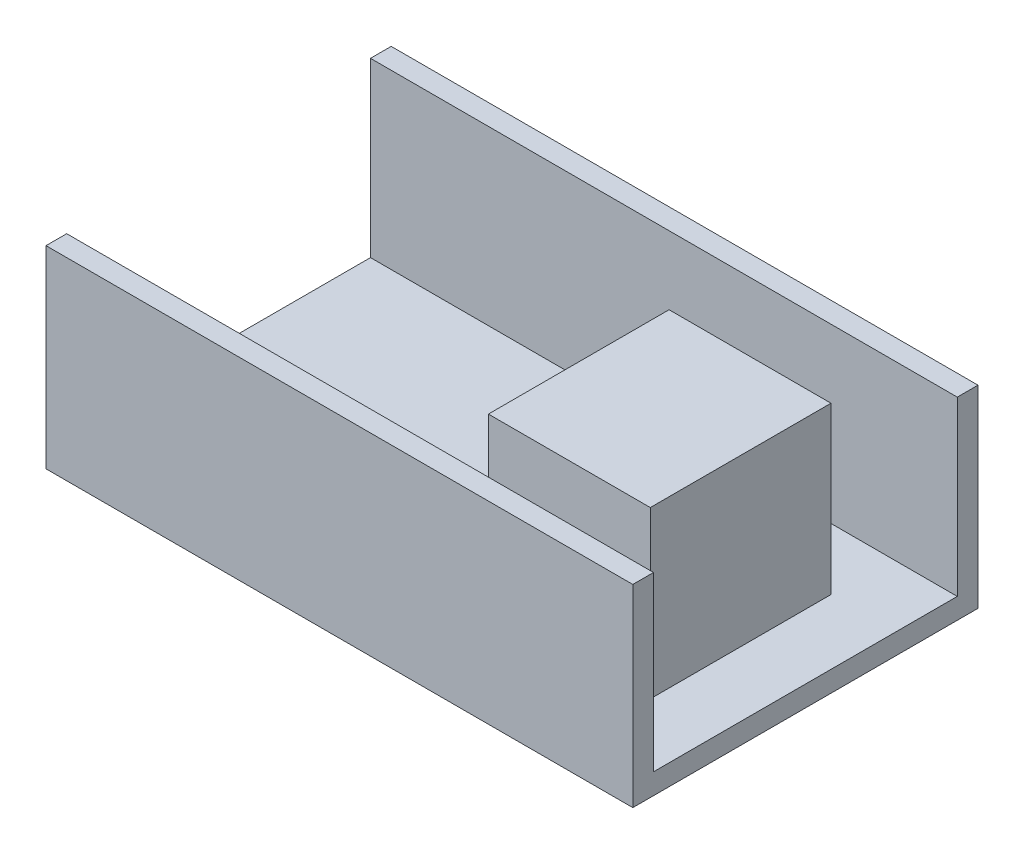
SolidWorks part; units mm, degrees
ref_plane "前视基准面" through (0, 0, 0) normal (0, 0, 1) x (1, 0, 0)
ref_plane "上视基准面" through (0, 0, 0) normal (0, 1, 0) x (1, 0, 0)
ref_plane "右视基准面" through (0, 0, 0) normal (1, 0, 0) x (0, 0, -1)
sketch "草图1" plane through (0, 0, 0) normal (1, 0, 0) x (0, 0, -1)
  line L0 (25, 28) -> (25, 0)
  line L1 (0, 0) -> (0, 41.8298) construction
  line L2 (-25, 28) -> (-25, 0)
  line L3 (-25, 0) -> (25, 0)
  dimension "D1" = 50
  dimension "D2" = 28
extrude "拉伸-薄壁1" add sketch "草图1" against normal mid plane 85 thin
sketch "草图2" plane through (0, 3, 0) normal (0, 1, 0) x (1, 0, 0)
  line L1 (9.6672, -13.0869) -> (33.1195, -13.0869)
  line L2 (9.6672, -13.0869) -> (9.6672, 13.0869)
  line L3 (9.6672, 13.0869) -> (33.1195, 13.0869)
  line L4 (33.1195, -13.0869) -> (33.1195, 13.0869)
  line L5 (9.6672, -13.0869) -> (33.1195, 13.0869) construction
  line L6 (9.6672, 13.0869) -> (33.1195, -13.0869) construction
  point P0 (21.3933, 0)
extrude "凸台-拉伸1" add sketch "草图2" along normal blind 24
